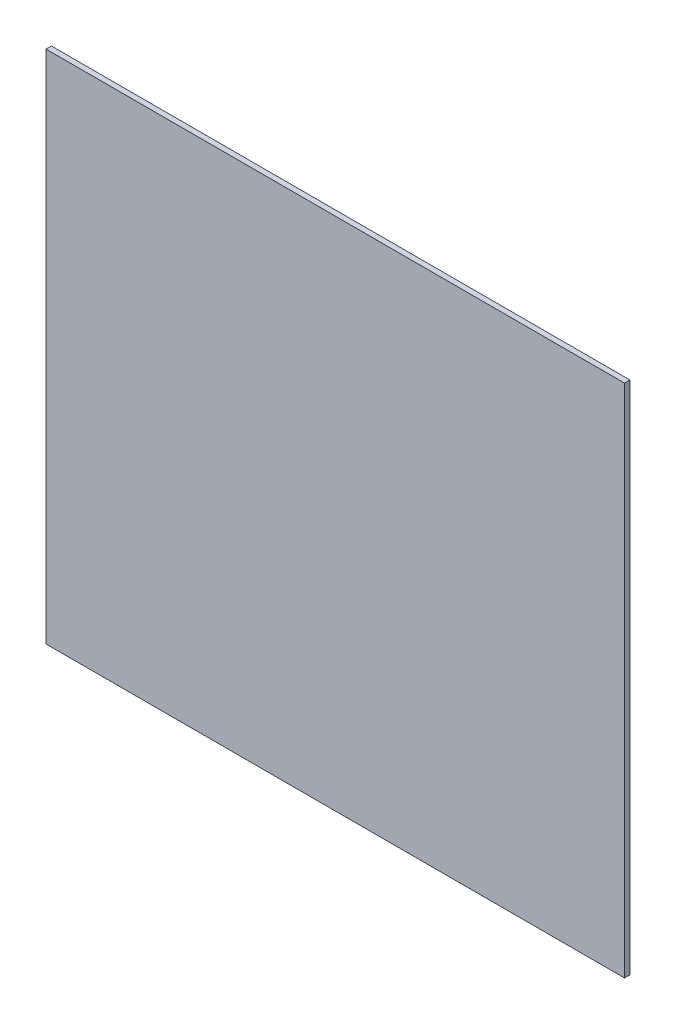
SolidWorks part; units mm, degrees
ref_plane "Front Plane" through (0, 0, 0) normal (0, 0, 1) x (1, 0, 0)
ref_plane "Top Plane" through (0, 0, 0) normal (0, 1, 0) x (1, 0, 0)
ref_plane "Right Plane" through (0, 0, 0) normal (1, 0, 0) x (0, 0, -1)
sketch "Sketch1" plane through (0, 0, 0) normal (0, 0, 1) x (1, 0, 0)
  line L1 (-160, -142.5) -> (160, -142.5)
  line L2 (-160, -142.5) -> (-160, 142.5)
  line L3 (-160, 142.5) -> (160, 142.5)
  line L4 (160, -142.5) -> (160, 142.5)
  line L5 (-160, -142.5) -> (160, 142.5) construction
  line L6 (-160, 142.5) -> (160, -142.5) construction
  point P0 (0, 0)
  dimension "D1" = 285
  dimension "D2" = 320
extrude "Boss-Extrude1" add sketch "Sketch1" along normal blind 3
equation "\"PCWidth\"= 172mm"
equation "\"PCLength\"= 320mm"
equation "\"PCHeight\"= 242mm"
equation "\"WallThickness\"= 10mm"
equation "\"ThermoBarrierThickness\"= 3mm"
equation "\"HotSideGap\"= 50mm"
equation "\"PCClearance\"= 25mm"
equation "\"RadiatorHeight\"= 275mm"
equation "\"D1@Sketch1\"=\"RadiatorHeight\" + 10"
equation "\"D2@Sketch1\"=\"PCLength\""
equation "\"D1@Boss-Extrude1\"=\"ThermoBarrierThickness\""
